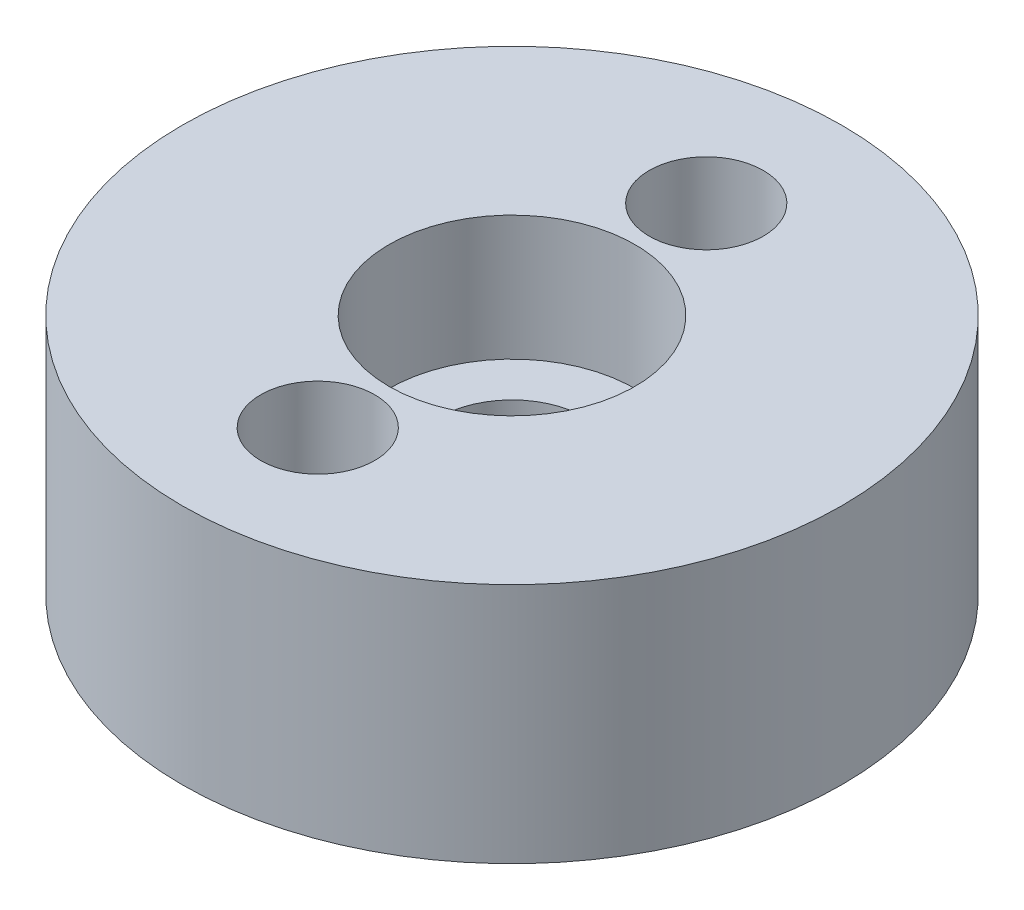
SolidWorks part; units mm, degrees
ref_plane "Front Plane" through (0, 0, 0) normal (0, 0, 1) x (1, 0, 0)
ref_plane "Top Plane" through (0, 0, 0) normal (0, 1, 0) x (1, 0, 0)
ref_plane "Right Plane" through (0, 0, 0) normal (1, 0, 0) x (0, 0, -1)
sketch "Sketch1" plane through (0, 0, 0) normal (0, 1, 0) x (1, 0, 0)
  circle A0 centre (0, 0) radius 9.25
extrude "Boss-Extrude1" add sketch "Sketch1" along normal blind 6.78
sketch "Sketch2" plane through (0, 6.78, 0) normal (0, 1, 0) x (1, 0, 0)
  circle A0 centre (0, 0) radius 2.05
extrude "Cut-Extrude1" cut sketch "Sketch2" against normal through all
sketch "Sketch3" plane through (0, 6.78, 0) normal (0, 1, 0) x (1, 0, 0)
  circle A0 centre (0, 0) radius 3.45
extrude "Cut-Extrude2" cut sketch "Sketch3" against normal blind 3.5
sketch "Sketch4" plane through (0, 0, 0) normal (0, -1, 0) x (-1, 0, 0)
  circle A0 centre (0, 5.45) radius 1.6
  dimension "D1" = 5.45
extrude "Cut-Extrude3" cut sketch "Sketch4" against normal through all
pattern_circular "CirPattern1" count 2 over 360 about axis through (0, 0, 0) along (0, 1, 0) of "Cut-Extrude3"
sketch "Sketch5" plane through (0, 0, 0) normal (0, -1, 0) x (-1, 0, 0)
  circle A0 centre (0, 5.45) radius 2.75
extrude "Cut-Extrude4" cut sketch "Sketch5" against normal blind 3
pattern_circular "CirPattern2" count 2 over 360 about axis through (0, 0, 0) along (0, 1, 0) of "Cut-Extrude4"
